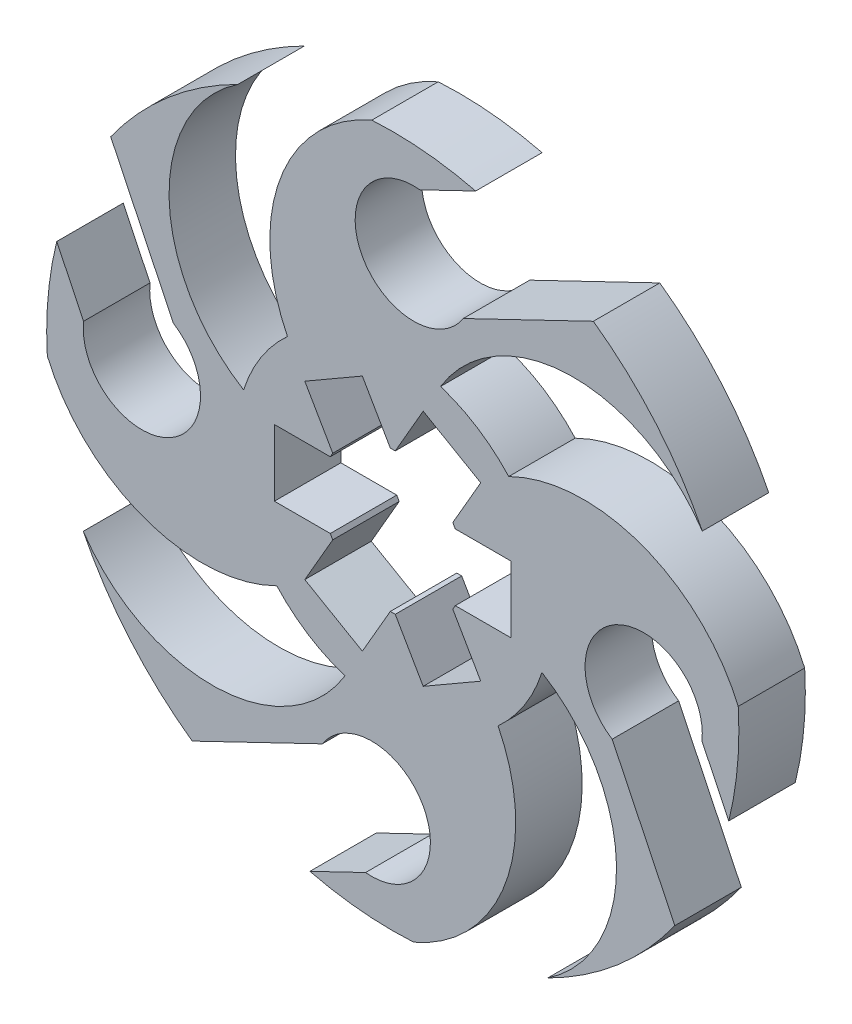
SolidWorks part; units mm, degrees
ref_plane "Front Plane" through (0, 0, 0) normal (0, 0, 1) x (1, 0, 0)
ref_plane "Top Plane" through (0, 0, 0) normal (0, 1, 0) x (1, 0, 0)
ref_plane "Right Plane" through (0, 0, 0) normal (1, 0, 0) x (0, 0, -1)
sketch "Sketch1" plane through (0, 0, 0) normal (0, 0, 1) x (1, 0, 0)
  line L0 (110.2077, 0) -> (110.2077, -1.524)
  line L1 (110.2077, -1.524) -> (108.9259, -1.524)
  line L2 (108.9259, -1.524) -> (108.8691, -1.6222)
  line L3 (108.8691, -1.6222) -> (109.51, -2.7323)
  line L4 (109.51, -2.7323) -> (108.1902, -3.4943)
  line L5 (108.1902, -3.4943) -> (107.5493, -2.3842)
  line L6 (107.5493, -2.3842) -> (107.4359, -2.3842)
  line L7 (107.4359, -2.3842) -> (106.795, -3.4943)
  line L8 (106.795, -3.4943) -> (105.4751, -2.7323)
  line L9 (105.4751, -2.7323) -> (106.116, -1.6222)
  line L10 (106.116, -1.6222) -> (106.0593, -1.524)
  line L11 (106.0593, -1.524) -> (104.7775, -1.524)
  line L12 (104.7775, -1.524) -> (104.7775, 0)
  line L13 (104.7775, 0) -> (106.0593, 0)
  line L14 (106.0593, 0) -> (106.116, 0.0982)
  line L15 (106.116, 0.0982) -> (105.4751, 1.2083)
  line L16 (105.4751, 1.2083) -> (106.795, 1.9703)
  line L17 (106.795, 1.9703) -> (107.4359, 0.8602)
  line L18 (107.4359, 0.8602) -> (107.5493, 0.8602)
  line L19 (107.5493, 0.8602) -> (108.1902, 1.9703)
  line L20 (108.1902, 1.9703) -> (109.51, 1.2083)
  line L21 (109.51, 1.2083) -> (108.8691, 0.0982)
  line L22 (105.5914, -8.4685) -> (106.8691, -7.8532)
  line L23 (108.8691, 0.0982) -> (108.9259, 0)
  line L24 (108.9259, 0) -> (110.2077, 0)
  line L25 (115.199, -2.6632) -> (114.5838, -1.3855)
  line L26 (113.9614, -5.3619) -> (112.5241, -2.3773)
  line L27 (102.8927, -7.2308) -> (105.8773, -5.7936)
  line L28 (99.7861, 1.1392) -> (100.4014, -0.1385)
  line L29 (101.0238, 3.8379) -> (102.461, 0.8533)
  line L30 (109.3938, 6.9445) -> (108.1161, 6.3292)
  line L31 (112.0925, 5.7068) -> (109.1079, 4.2696)
  arc A0 (114.5913, 2.7894) -> (112.0925, 5.7068) centre (107.4926, -0.762) ccw
  arc A1 (100.3939, -4.3134) -> (106.3973, -4.1831) centre (103.354, -2.3302) ccw
  arc A2 (109.9077, -3.4211) -> (107.9741, -8.6849) centre (106.4564, -5.1403) cw
  arc A3 (103.9412, 6.3367) -> (104.0714, 0.3333) centre (105.9244, 3.3766) ccw
  arc A4 (104.8334, -3.1771) -> (99.5697, -1.2436) centre (103.1142, 0.2742) cw
  arc A5 (114.5913, 2.7894) -> (108.5879, 2.6591) centre (111.6312, 0.8062) ccw
  arc A6 (105.0775, 1.8971) -> (107.011, 7.1609) centre (108.5288, 3.6163) cw
  arc A7 (111.044, -7.8607) -> (110.9137, -1.8573) centre (109.0608, -4.9006) ccw
  arc A8 (110.1517, 1.6531) -> (115.4155, -0.2804) centre (111.8709, -1.7982) cw
  arc A9 (111.044, -7.8607) -> (113.9614, -5.3619) centre (107.4926, -0.762) ccw
  arc A10 (100.3939, -4.3134) -> (102.8927, -7.2308) centre (107.4926, -0.762) ccw
  circle A11 centre (107.4926, -0.762) radius 2.7151 construction
  arc A12 (104.8334, -3.1771) -> (106.3973, -4.1831) centre (107.4926, -0.762) ccw
  arc A13 (105.0775, 1.8971) -> (104.0714, 0.3333) centre (107.4926, -0.762) ccw
  arc A14 (110.1517, 1.6531) -> (108.5879, 2.6591) centre (107.4926, -0.762) ccw
  arc A15 (109.9077, -3.4211) -> (110.9137, -1.8573) centre (107.4926, -0.762) ccw
  arc A16 (103.9412, 6.3367) -> (101.0238, 3.8379) centre (107.4926, -0.762) ccw
  arc A17 (114.5838, -1.3855) -> (112.5241, -2.3773) centre (113.2468, -1.2436) ccw
  arc A18 (115.199, -2.6632) -> (115.4155, -0.2804) centre (107.4926, -0.762) ccw
  arc A19 (106.8691, -7.8532) -> (105.8773, -5.7936) centre (107.011, -6.5162) ccw
  arc A20 (100.4014, -0.1385) -> (102.461, 0.8533) centre (101.7384, -0.2804) ccw
  arc A21 (108.1161, 6.3292) -> (109.1079, 4.2696) centre (107.9741, 4.9922) ccw
  arc A22 (105.5914, -8.4685) -> (107.9741, -8.6849) centre (107.4926, -0.762) ccw
  arc A23 (99.7861, 1.1392) -> (99.5697, -1.2436) centre (107.4926, -0.762) ccw
  arc A24 (109.3938, 6.9445) -> (107.011, 7.1609) centre (107.4926, -0.762) ccw
  point P47 (116.4599, -5.2815)
  point P49 (114.2766, -0.7476)
  point P58 (107.4926, -0.762)
  point P59 (114.4003, -6.2733)
  point P60 (112.217, -1.7395)
  point P82 (107.4926, -0.762)
  dimension "D1" = 15.875
extrude "Boss-Extrude1" add sketch "Sketch1" along normal blind 1.524
